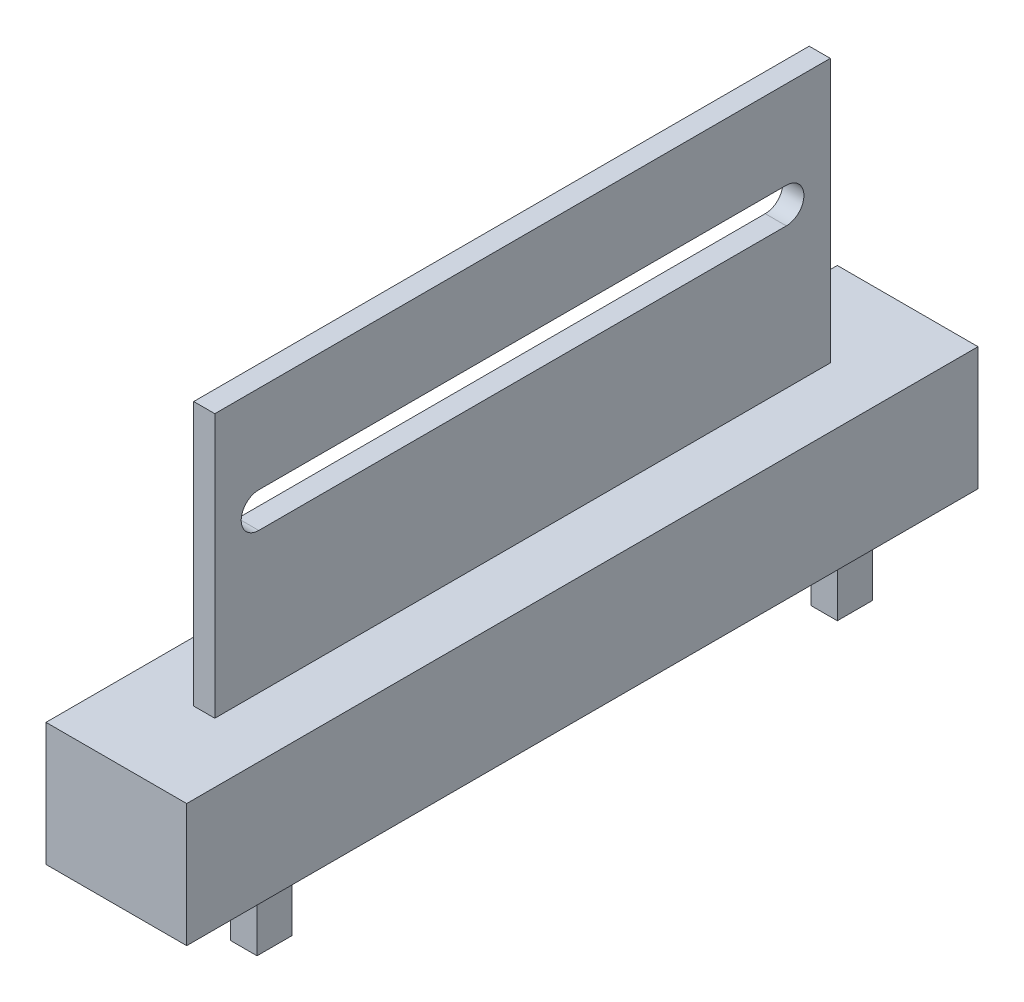
SolidWorks part; units mm, degrees
ref_plane "Front Plane" through (0, 0, 0) normal (0, 0, 1) x (1, 0, 0)
ref_plane "Top Plane" through (0, 0, 0) normal (0, 1, 0) x (1, 0, 0)
ref_plane "Right Plane" through (0, 0, 0) normal (1, 0, 0) x (0, 0, -1)
sketch "Sketch1" plane through (0, 0, 0) normal (1, 0, 0) x (0, 0, -1)
  line L1 (0, 0) -> (45, 0)
  line L2 (0, 0) -> (0, 7)
  line L3 (0, 7) -> (45, 7)
  line L4 (45, 0) -> (45, 7)
  dimension "D1" = 7
  dimension "D2" = 45
extrude "Boss-Extrude1" add sketch "Sketch1" along normal mid plane 8
sketch "Sketch2" plane through (0, 7, 0) normal (0, 1, 0) x (1, 0, 0)
  line L0 (0, 45) -> (0, 0) construction
  line L1 (4, 45) -> (-4, 45) construction
  line L2 (0, 40) -> (0, 5) construction
  line L3 (-0.6, 40) -> (0.6, 40)
  line L4 (-0.6, 40) -> (-0.6, 5)
  line L5 (-0.6, 5) -> (0.6, 5)
  line L6 (0.6, 40) -> (0.6, 5)
  point P11 (0, 22.5)
  point P12 (0, 22.5)
  dimension "D1" = 1.2
  dimension "D2" = 5
extrude "Boss-Extrude2" add sketch "Sketch2" along normal blind 15 separate body
sketch "Sketch3" plane through (0, 0, 0) normal (0, -1, 0) x (1, 0, 0)
  line L0 (-1.5, -6) -> (1.5, -6) construction
  line L1 (-4, 0) -> (-4, -45) construction
  line L2 (0, 0) -> (0, -45) construction
  line L3 (4, 0) -> (4, -45) construction
  line L4 (-4, -22.5) -> (4, -22.5) construction
  line L5 (-3, -7) -> (-1.5, -7)
  line L6 (-3, -7) -> (-3, -5)
  line L7 (-3, -5) -> (-1.5, -5)
  line L8 (-1.5, -7) -> (-1.5, -5)
  line L9 (1.5, -5) -> (3, -5)
  line L10 (1.5, -5) -> (1.5, -7)
  line L11 (1.5, -7) -> (3, -7)
  line L12 (3, -5) -> (3, -7)
  line L13 (-1.5, -39) -> (1.5, -39) construction
  line L15 (3, -40) -> (3, -38)
  line L16 (1.5, -38) -> (3, -38)
  line L17 (1.5, -40) -> (1.5, -38)
  line L18 (1.5, -40) -> (3, -40)
  line L19 (-1.5, -38) -> (-1.5, -40)
  line L20 (-3, -40) -> (-1.5, -40)
  line L21 (-3, -38) -> (-3, -40)
  line L22 (-3, -38) -> (-1.5, -38)
  point P4 (0, -6)
  point P16 (-1.5, -6)
  point P17 (3, -6)
  point P24 (0, -22.5)
  dimension "D1" = 1.5
  dimension "D2" = 1
  dimension "D3" = 2
  dimension "D4" = 5
extrude "Boss-Extrude3" add sketch "Sketch3" along normal blind 3.5 separate body
sketch "Sketch4" plane through (0.6, 0, 0) normal (1, 0, 0) x (0, 0, -1)
  line L0 (7.5, 16) -> (37.5, 16) construction
  line L1 (7.5, 17) -> (37.5, 17)
  line L2 (7.5, 15) -> (37.5, 15)
  line L3 (0, 7) -> (0, 0) construction
  line L4 (45, 0) -> (45, 7) construction
  line L6 (5, 7) -> (40, 7) construction
  arc A0 (7.5, 17) -> (7.5, 15) centre (7.5, 16) ccw
  arc A1 (37.5, 15) -> (37.5, 17) centre (37.5, 16) ccw
  point P2 (22.5, 16)
  dimension "D1" = 2
  dimension "D2" = 7.5
  dimension "D3" = 7.5
  dimension "D4" = 8
extrude "Cut-Extrude1" cut sketch "Sketch4" against normal blind 10
sketch "Sketch5" plane through (0, 0, 0) normal (1, 0, 0) x (0, 0, -1)
  line L0 (7.5, 16) -> (37.5, 16) construction
